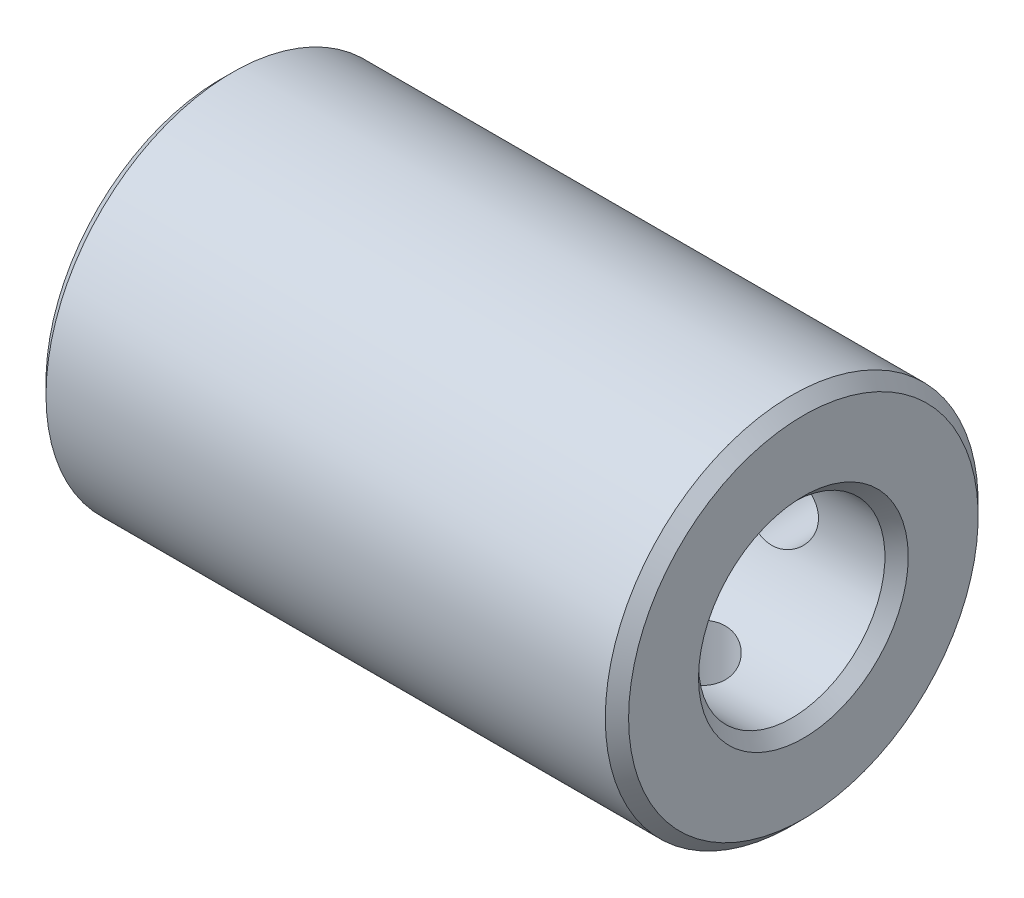
SolidWorks part; units mm, degrees
ref_plane "前视基准面" through (0, 0, 0) normal (0, 0, 1) x (1, 0, 0)
ref_plane "上视基准面" through (0, 0, 0) normal (0, 1, 0) x (1, 0, 0)
ref_plane "右视基准面" through (0, 0, 0) normal (1, 0, 0) x (0, 0, -1)
sketch "草图1" plane through (0, 0, 0) normal (0, 1, 0) x (1, 0, 0)
  line L0 (-10.5247, 0) -> (10.2778, 0)
  line L1 (0, 8.5494) -> (0, -6.358)
  line L2 (0, 2.5) -> (12.5, 2.5)
  line L3 (12.5, 2.5) -> (12.5, 4)
  line L4 (12.5, 4) -> (25, 4)
  line L5 (25, 4) -> (25, 8)
  line L6 (25, 8) -> (0, 8)
  dimension "D1" = 2.5
  dimension "D2" = 4
  dimension "D3" = 8
  dimension "D4" = 25
  dimension "D5" = 12.5
revolve "旋转1" add sketch "草图1" angle 360 about L0
chamfer "倒角1" distance 0.5 angle 45 5 edges at (0, 0, 2.5) (12.5, 0, 2.5) (25, 0, 4) (0, 0, 8) (25, 0, 8)
sketch "草图2" plane through (0, 0, 0) normal (0, 1, 0) x (1, 0, 0)
  line L0 (-3.9253, 0) -> (28.3087, 0) construction
  line L1 (0, 10.279) -> (0, -10.279) construction
  line L2 (25, 7.5) -> (25, -7.5) construction
  line L3 (5, 10.279) -> (5, -10.279) construction
  line L4 (20, 7.5) -> (20, -7.5) construction
  circle A0 centre (5, 0) radius 1.65
  circle A1 centre (20, 0) radius 1.65
  dimension "D3" = 3.3
  dimension "D4" = 3.3
  dimension "D1" = 5
  dimension "D2" = 5
extrude "切除-拉伸1" cut sketch "草图2" against normal blind 10
sketch "草图3" plane through (0, 0, 0) normal (0, 0, 1) x (1, 0, 0)
  line L0 (-2.6359, 0) -> (28.2152, 0) construction
  line L1 (0, 7.5) -> (0, -7.5) construction
  line L2 (0, -7.5) -> (0.5, -8) construction
  line L3 (0, 7.5) -> (0, -7.5) construction
  line L4 (25, 7.5) -> (25, -7.5) construction
  line L5 (5, 7.5) -> (5, -7.5) construction
  line L6 (20, 7.5) -> (20, -7.5) construction
  circle A0 centre (5, 0) radius 1.65
  circle A1 centre (20, 0) radius 1.65
  dimension "D3" = 3.3
  dimension "D4" = 3.3
  dimension "D1" = 5
  dimension "D2" = 5
extrude "切除-拉伸2" cut sketch "草图3" against normal blind 10
